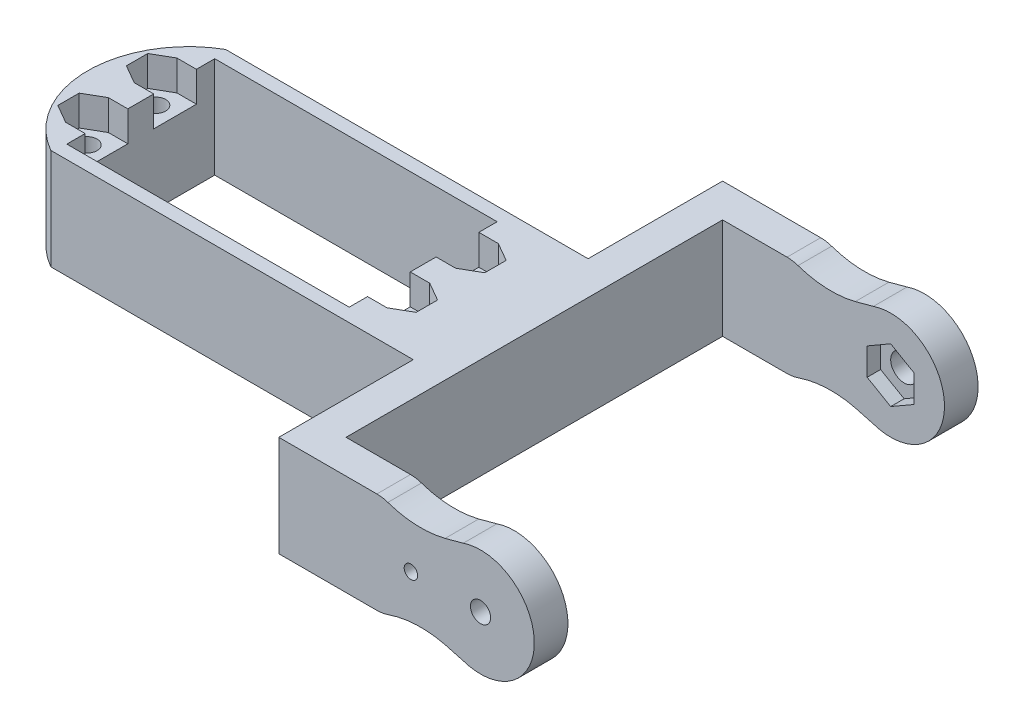
SolidWorks part; units mm, degrees
ref_plane "Plan de face" through (0, 0, 0) normal (0, 0, 1) x (1, 0, 0)
ref_plane "Plan de dessus" through (0, 0, 0) normal (0, 1, 0) x (1, 0, 0)
ref_plane "Plan de droite" through (0, 0, 0) normal (1, 0, 0) x (0, 0, -1)
sketch "Esquisse1" plane through (0, 0, 0) normal (0, 0, 1) x (1, 0, 0)
  line L1 (-23.2387, 9.5601) -> (56.7613, 9.5601)
  line L2 (-23.2387, 9.5601) -> (-23.2387, -16.4399)
  line L3 (-23.2387, -16.4399) -> (56.7613, -16.4399)
  line L4 (56.7613, 9.5601) -> (56.7613, -16.4399)
  dimension "D1" = 26
  dimension "D2" = 80
extrude "Boss.-Extru.1" add sketch "Esquisse1" along normal blind 5
sketch "Esquisse4" plane through (0, 0, 0) normal (0, 0, -1) x (-1, 0, 0)
  line L0 (23.2387, 9.5601) -> (23.2387, -16.4399) construction
  line L1 (38.2387, -13.9399) -> (23.2387, -13.9399)
  line L2 (38.2387, -13.9399) -> (38.2387, 7.0601)
  line L3 (38.2387, 7.0601) -> (23.2387, 7.0601)
  line L4 (23.2387, -13.9399) -> (23.2387, 7.0601)
  line L5 (23.2387, -16.4399) -> (-56.7613, -16.4399) construction
  line L6 (-56.7613, 9.5601) -> (23.2387, 9.5601) construction
  dimension "D1" = 0
  dimension "D2" = 2.5
  dimension "D3" = 2.5
  dimension "D4" = 15
extrude "Boss.-Extru.2" add sketch "Esquisse4" against normal blind 23
sketch "Esquisse6" plane through (0, -13.9399, 0) normal (0, -1, 0) x (1, 0, 0)
  line L0 (-23.2387, 23) -> (-23.2387, 5) construction
  line L1 (-23.2387, 0) -> (-38.2387, 0) construction
  circle A0 centre (-28.7387, 5) radius 1.9
  dimension "D2" = 5
  dimension "D3" = 3.8
  dimension "D1" = 5.5
extrude "Enlèv. mat.-Extru.1" cut sketch "Esquisse6" against normal blind 23
sketch "Esquisse7" plane through (0, 0, 23) normal (0, 0, 1) x (1, 0, 0)
  line L0 (-23.2387, 7.0601) -> (-23.2387, -13.9399) construction
  line L1 (-38.2387, 7.0601) -> (-23.2387, 7.0601) construction
  circle A0 centre (-33.2387, -3.4399) radius 2.5
  dimension "D1" = 5
  dimension "D2" = 10
  dimension "D3" = 10.5
extrude "Enlèv. mat.-Extru.2" cut sketch "Esquisse7" against normal blind 33
sketch "Esquisse8" plane through (0, 0, 0) normal (0, 0, -1) x (-1, 0, 0)
  line L0 (23.2387, -13.9399) -> (38.2387, -13.9399) construction
  line L1 (50.0831, -10.9399) -> (26.2387, -10.9399)
  line L2 (50.0831, -10.9399) -> (50.0831, 4.0601)
  line L3 (50.0831, 4.0601) -> (26.2387, 4.0601)
  line L4 (26.2387, -10.9399) -> (26.2387, 4.0601)
  line L5 (38.2387, 7.0601) -> (23.2387, 7.0601) construction
  line L6 (23.2387, -13.9399) -> (23.2387, -16.4399) construction
  dimension "D1" = 3
  dimension "D2" = 3
  dimension "D3" = 3
extrude "Enlèv. mat.-Extru.3" cut sketch "Esquisse8" against normal blind 20
sketch "Esquisse9" plane through (0, 0, 0) normal (0, 0, -1) x (-1, 0, 0)
  line L19 (38.2387, -13.9399) -> (38.2387, -10.9399)
  line L20 (38.2387, -10.9399) -> (26.2387, -10.9399)
  line L21 (26.2387, -10.9399) -> (26.2387, 4.0601)
  line L22 (26.2387, 4.0601) -> (38.2387, 4.0601)
  line L23 (38.2387, 4.0601) -> (38.2387, 7.0601)
  line L24 (38.2387, 7.0601) -> (23.2387, 7.0601)
  line L25 (23.2387, 7.0601) -> (23.2387, 9.5601)
  line L26 (23.2387, 9.5601) -> (-56.7613, 9.5601)
  line L27 (-56.7613, 9.5601) -> (-56.7613, -16.4399)
  line L28 (-56.7613, -16.4399) -> (23.2387, -16.4399)
  line L29 (23.2387, -16.4399) -> (23.2387, -13.9399)
  line L30 (23.2387, -13.9399) -> (38.2387, -13.9399)
  line L37 (23.2387, 7.0601) -> (23.2387, 9.5601)
  line L38 (23.2387, 9.5601) -> (17.8135, 9.5601)
  line L40 (17.8135, -16.4399) -> (23.2387, -16.4399)
  line L41 (23.2387, -16.4399) -> (23.2387, -13.9399)
  arc A3 (17.8135, -16.4399) -> (23.2387, -13.9399) centre (17.8135, -9.3033) ccw
  arc A4 (17.8135, 9.5601) -> (23.2387, 7.0601) centre (17.8135, 2.4236) cw
  dimension "D1" = 0
extrude "Enlèv. mat.-Extru.4" cut sketch "Esquisse9" against normal blind 20
sketch "Esquisse10" plane through (0, -13.9399, 0) normal (0, -1, 0) x (1, 0, 0)
  line L5 (-38.2387, 0) -> (-23.2387, 0)
  line L6 (-23.2387, 0) -> (-23.2387, 5)
  line L7 (-23.2387, 5) -> (-23.2387, 23)
  line L8 (-23.2387, 23) -> (-38.2387, 23)
  line L9 (-38.2387, 23) -> (-38.2387, 0)
  line L12 (-23.2387, 21.5) -> (-23.2387, 23)
  line L13 (-23.2387, 23) -> (-24.7387, 23)
  arc A0 (-23.2387, 21.5) -> (-24.7387, 23) centre (-24.7387, 21.5) ccw
  dimension "D2" = 3
  dimension "D1" = 0
extrude "Enlèv. mat.-Extru.5" cut sketch "Esquisse10" against normal blind 25
sketch "Esquisse12" plane through (0, -13.9399, 0) normal (0, -1, 0) x (1, 0, 0)
  line L0 (-24.7387, 23) -> (-38.2387, 23) construction
  line L1 (-38.2387, 23) -> (-36.7387, 23)
  line L2 (-38.2387, 23) -> (-38.2387, 21.5)
  arc A0 (-36.7387, 23) -> (-38.2387, 21.5) centre (-36.7387, 21.5) ccw
  dimension "D1" = 3
  dimension "D3" = 1.5
extrude "Enlèv. mat.-Extru.7" cut sketch "Esquisse12" against normal blind 25
sketch "Esquisse13" plane through (0, 7.0601, 0) normal (0, 1, 0) x (1, 0, 0)
  line L1 (-30.7594, -1.5) -> (-32.7801, -5)
  line L2 (-32.7801, -5) -> (-30.7594, -8.5)
  line L3 (-30.7594, -8.5) -> (-26.718, -8.5)
  line L4 (-26.718, -8.5) -> (-24.6972, -5)
  line L5 (-24.6972, -5) -> (-26.718, -1.5)
  line L6 (-26.718, -1.5) -> (-30.7594, -1.5)
  circle A0 centre (-28.7387, -5) radius 3.5 construction
  circle A1 centre (-28.7387, -5) radius 1.9 construction
  dimension "D1" = 7
extrude "Enlèv. mat.-Extru.8" cut sketch "Esquisse13" against normal blind 1
sketch "Esquisse14" plane through (0, 7.0601, 0) normal (0, 1, 0) x (1, 0, 0)
  line L0 (-30.7594, -1.5) -> (-32.7801, -5) construction
  line L1 (-26.718, -1.5) -> (-30.7594, -1.5) construction
  line L2 (-24.6972, -5) -> (-26.718, -1.5) construction
  line L3 (-26.718, -8.5) -> (-24.6972, -5) construction
  line L4 (-30.7594, -8.5) -> (-26.718, -8.5) construction
  line L6 (-25.8519, 0) -> (-31.6254, 0)
  line L7 (-31.6254, 0) -> (-34.5122, -5)
  line L8 (-34.5122, -5) -> (-31.6254, -10)
  line L9 (-31.6254, -10) -> (-25.8519, -10)
  line L15 (-32.7801, -5) -> (-30.7594, -8.5) construction
  line L16 (-30.7594, -1.5) -> (-32.7801, -5)
  line L17 (-26.718, -1.5) -> (-30.7594, -1.5)
  line L18 (-24.6972, -5) -> (-26.718, -1.5)
  line L19 (-26.718, -8.5) -> (-24.6972, -5)
  line L20 (-30.7594, -8.5) -> (-26.718, -8.5)
  line L21 (-32.7801, -5) -> (-30.7594, -8.5)
  line L22 (-25.8519, -10) -> (-23.2387, -5.4737)
  line L27 (-23.2387, -4.5263) -> (-25.8519, 0)
  line L28 (-38.2387, 0) -> (-23.2387, 0) construction
  line L29 (-23.2387, -4.5263) -> (-23.2387, -5.4737)
  line L30 (-23.2387, -21.5) -> (-23.2387, -5) construction
  circle A1 centre (-28.7387, -5) radius 5 construction
  circle A2 centre (-28.7387, -5) radius 1.9 construction
extrude "Boss.-Extru.3" add sketch "Esquisse14" along normal blind 2
sketch "Esquisse15" plane through (0, 0, 0) normal (0, 0, -1) x (-1, 0, 0)
  circle A7 centre (-51.7613, -8.5399) radius 1.5
  circle A8 centre (-51.7613, 1.6601) radius 1.5
  circle A9 centre (-3.9613, -8.5399) radius 1.5
  circle A10 centre (-3.9613, 1.6601) radius 1.5
  dimension "D10" = 3
extrude "Enlèv. mat.-Extru.9" cut sketch "Esquisse15" against normal blind 19
sketch "Esquisse16" plane through (0, 0, 0) normal (0, 0, -1) x (-1, 0, 0)
  line L0 (17.8135, -16.4399) -> (-56.7613, -16.4399) construction
  line L1 (-56.7613, -16.4399) -> (-56.7613, 9.5601) construction
  line L2 (-43.3764, 11.4729) -> (-43.3764, 11.5601)
  line L3 (-43.3764, -43.1341) -> (-70.7923, -43.1341)
  line L4 (-43.3764, -43.1341) -> (-43.3764, -18.3527)
  line L5 (-43.3764, 11.5601) -> (-70.7923, 11.5601)
  line L6 (-70.7923, -43.1341) -> (-70.7923, 11.5601)
  arc A0 (-43.3764, 11.4729) -> (-43.3764, -18.3527) centre (-41.7613, -3.4399) ccw
  dimension "D1" = 13
  dimension "D2" = 30
  dimension "D3" = 15
extrude "Enlèv. mat.-Extru.10" cut sketch "Esquisse16" against normal blind 19
sketch "Esquisse17" plane through (0, 0, 5) normal (0, 0, 1) x (1, 0, 0)
  line L0 (49.2446, 9.5601) -> (-17.8135, 9.5601) construction
  line L1 (6.8613, 7.5601) -> (48.8613, 7.5601)
  line L2 (6.8613, 7.5601) -> (6.8613, -14.4399)
  line L3 (6.8613, -14.4399) -> (48.8613, -14.4399)
  line L4 (48.8613, 7.5601) -> (48.8613, -14.4399)
  circle A0 centre (3.9613, 1.6601) radius 1.5 construction
  dimension "D4" = 2.9
  dimension "D1" = 42
  dimension "D2" = 22
  dimension "D3" = 2
extrude "Enlèv. mat.-Extru.11" cut sketch "Esquisse17" against normal blind 19
sketch "Esquisse18" plane through (0, 0, 0) normal (0, 0, -1) x (-1, 0, 0)
  line L13 (-49.0113, 3.2479) -> (-51.7613, 4.8356)
  line L14 (-51.7613, 4.8356) -> (-54.5113, 3.2479)
  line L15 (-54.5113, 3.2479) -> (-54.5113, 0.0724)
  line L16 (-54.5113, 0.0724) -> (-51.7613, -1.5153)
  line L17 (-51.7613, -1.5153) -> (-49.0113, 0.0724)
  line L19 (-49.0113, -6.9521) -> (-51.7613, -5.3644)
  line L20 (-51.7613, -5.3644) -> (-54.5113, -6.9521)
  line L21 (-54.5113, -6.9521) -> (-54.5113, -10.1276)
  line L22 (-54.5113, -10.1276) -> (-51.7613, -11.7153)
  line L23 (-51.7613, -11.7153) -> (-49.0113, -10.1276)
  line L25 (-49.0113, -10.1276) -> (-46.2613, -8.5399)
  line L26 (-46.2613, -8.5399) -> (-49.0113, -6.9521)
  line L28 (-49.0113, 3.2479) -> (-46.2613, 1.6601)
  line L29 (-49.0113, 0.0724) -> (-46.2613, 1.6601)
  line L30 (-49.0113, -10.1276) -> (-49.0113, -8.5399) [skipped]
  line L31 (-49.0113, 0.0724) -> (-49.0113, 1.6601) [skipped]
  line L33 (-6.7113, 0.0724) -> (-9.4613, 1.6601)
  line L34 (-6.7113, 3.2479) -> (-9.4613, 1.6601)
  line L35 (-9.4613, -8.5399) -> (-6.7113, -6.9521)
  line L36 (-6.7113, -10.1276) -> (-9.4613, -8.5399)
  line L37 (-3.9613, -11.7153) -> (-6.7113, -10.1276)
  line L38 (-1.2113, -10.1276) -> (-3.9613, -11.7153)
  line L39 (-1.2113, -6.9521) -> (-1.2113, -10.1276)
  line L40 (-3.9613, -5.3644) -> (-1.2113, -6.9521)
  line L41 (-6.7113, -6.9521) -> (-3.9613, -5.3644)
  line L42 (-3.9613, -1.5153) -> (-6.7113, 0.0724)
  line L43 (-1.2113, 0.0724) -> (-3.9613, -1.5153)
  line L44 (-1.2113, 3.2479) -> (-1.2113, 0.0724)
  line L45 (-3.9613, 4.8356) -> (-1.2113, 3.2479)
  line L46 (-6.7113, 3.2479) -> (-3.9613, 4.8356)
  arc A0 (-5.3363, -6.1583) -> (-5.3363, -10.9214) centre (-3.9613, -8.5399) cw construction
  arc A1 (-5.3363, 4.0417) -> (-5.3363, -0.7214) centre (-3.9613, 1.6601) cw construction
  arc A2 (-50.3863, 4.0417) -> (-50.3863, -0.7214) centre (-51.7613, 1.6601) ccw construction
  arc A3 (-50.3863, -6.1583) -> (-50.3863, -10.9214) centre (-51.7613, -8.5399) ccw construction
  circle A6 centre (-51.7613, 1.6601) radius 1.5 construction
  circle A7 centre (-51.7613, -8.5399) radius 1.5 construction
  dimension "D1" = 5.5
  dimension "D2" = 5.5
extrude "Enlèv. mat.-Extru.12" cut sketch "Esquisse18" against normal blind 2
sketch "Esquisse19" plane through (0, 0, 0) normal (0, 0, -1) x (-1, 0, 0)
  line L9 (-12.8613, -16.4399) -> (-22.8613, -16.4399)
  line L12 (-11.8613, -15.4399) -> (-11.8613, -14.4399)
  line L13 (-11.8613, -14.4399) -> (-23.8613, -14.4399)
  line L21 (-23.8613, -15.4399) -> (-23.8613, -14.4399)
  line L22 (-6.8613, -10.041) -> (-6.8613, -14.4399) construction
  line L23 (-6.8613, -14.4399) -> (-48.8613, -14.4399) construction
  line L24 (17.8135, -16.4399) -> (-49.2446, -16.4399) construction
  line L27 (-23.8613, 8.5601) -> (-23.8613, 7.5601)
  line L28 (-11.8613, 7.5601) -> (-23.8613, 7.5601)
  line L29 (-11.8613, 8.5601) -> (-11.8613, 7.5601)
  line L30 (-12.8613, 9.5601) -> (-22.8613, 9.5601)
  arc A2 (-12.8613, -16.4399) -> (-11.8613, -15.4399) centre (-12.8613, -15.4399) ccw
  arc A3 (-23.8613, -15.4399) -> (-22.8613, -16.4399) centre (-22.8613, -15.4399) ccw
  arc A6 (-23.8613, 8.5601) -> (-22.8613, 9.5601) centre (-22.8613, 8.5601) cw
  arc A7 (-12.8613, 9.5601) -> (-11.8613, 8.5601) centre (-12.8613, 8.5601) cw
  point P4 (-17.8613, -16.4399)
  dimension "D3" = 0
  dimension "D4" = 0
  dimension "D5" = 2
  dimension "D1" = 10
  dimension "D2" = 11
  dimension "D6" = 2
extrude "Boss.-Extru.4" add sketch "Esquisse19" along normal blind 22
sketch "Esquisse23" plane through (0, 0, -22) normal (0, 0, -1) x (-1, 0, 0)
  line L0 (-6.8613, -10.041) -> (-6.8613, -14.4399) construction
  line L4 (-23.8613, 8.5601) -> (-23.8613, 7.5601)
  line L5 (-23.8613, 7.5601) -> (-11.8613, 7.5601)
  line L6 (-11.8613, 7.5601) -> (-11.8613, 8.5601)
  line L7 (-12.8613, 9.5601) -> (-22.8613, 9.5601)
  line L8 (-23.8613, 8.5601) -> (-23.8613, 7.5601)
  line L10 (-11.8613, 7.5601) -> (-11.8613, 8.5601)
  line L11 (-12.8613, 9.5601) -> (-22.8613, 9.5601)
  line L12 (-22.8613, -16.4399) -> (-12.8613, -16.4399)
  line L13 (-11.8613, -15.4399) -> (-11.8613, -14.4399)
  line L14 (-11.8613, -14.4399) -> (-23.8613, -14.4399)
  line L15 (-23.8613, -14.4399) -> (-23.8613, -15.4399)
  line L16 (-22.8613, -16.4399) -> (-12.8613, -16.4399)
  line L17 (-11.8613, -15.4399) -> (-11.8613, -14.4399)
  line L19 (-23.8613, -14.4399) -> (-23.8613, -15.4399)
  line L21 (-6.8613, -14.4399) -> (-11.8613, -14.4399) construction
  arc A0 (-10.1971, -9.8632) -> (-10.1971, 2.9835) centre (-17.8613, -3.4399) ccw
  arc A1 (-11.8613, 7.5601) -> (-10.1971, 2.9835) centre (-4.7363, 7.5601) ccw
  arc A2 (-22.8613, 9.5601) -> (-23.8613, 8.5601) centre (-22.8613, 8.5601) ccw
  arc A3 (-11.8613, 8.5601) -> (-12.8613, 9.5601) centre (-12.8613, 8.5601) ccw
  arc A4 (-22.8613, 9.5601) -> (-23.8613, 8.5601) centre (-22.8613, 8.5601) ccw
  arc A5 (-11.8613, 8.5601) -> (-12.8613, 9.5601) centre (-12.8613, 8.5601) ccw
  arc A6 (-23.8613, -15.4399) -> (-22.8613, -16.4399) centre (-22.8613, -15.4399) ccw
  arc A7 (-12.8613, -16.4399) -> (-11.8613, -15.4399) centre (-12.8613, -15.4399) ccw
  arc A8 (-23.8613, -15.4399) -> (-22.8613, -16.4399) centre (-22.8613, -15.4399) ccw
  arc A9 (-12.8613, -16.4399) -> (-11.8613, -15.4399) centre (-12.8613, -15.4399) ccw
  arc A10 (-23.8613, 7.5601) -> (-25.5255, 2.9835) centre (-30.9863, 7.5601) cw
  arc A11 (-23.8613, -14.4399) -> (-25.5255, -9.8632) centre (-30.9863, -14.4399) ccw
  arc A12 (-11.8613, -14.4399) -> (-10.1971, -9.8632) centre (-4.7363, -14.4399) cw
  arc A13 (-25.5255, 2.9835) -> (-25.5255, -9.8632) centre (-17.8613, -3.4399) ccw
  dimension "D3" = 20
  dimension "D5" = 11
  dimension "D4" = 11
  dimension "D1" = 0
  dimension "D2" = 0
extrude "Boss.-Extru.5" add sketch "Esquisse23" along normal blind 10
sketch "Esquisse25" plane through (0, 0, -32) normal (0, 0, -1) x (-1, 0, 0)
  circle A0 centre (-17.8613, -3.4399) radius 8
  arc A1 (-10.1971, -9.8632) -> (-10.1971, 2.9835) centre (-17.8613, -3.4399) ccw construction
  dimension "D1" = 16
extrude "Enlèv. mat.-Extru.13" cut sketch "Esquisse25" against normal blind 5
sketch "Esquisse26" plane through (0, 0, -27) normal (0, 0, -1) x (-1, 0, 0)
  circle A0 centre (-17.8613, -3.4399) radius 6
  circle A1 centre (-17.8613, -3.4399) radius 8 construction
  dimension "D1" = 12
extrude "Enlèv. mat.-Extru.14" cut sketch "Esquisse26" against normal blind 5
sketch "Esquisse29" plane through (0, -13.9399, 0) normal (0, -1, 0) x (1, 0, 0)
  line L0 (-23.2387, 0) -> (-38.2387, 0) construction
  line L1 (-26.718, 1.5) -> (-24.6972, 5)
  line L2 (-24.6972, 5) -> (-26.718, 8.5)
  line L3 (-26.718, 8.5) -> (-30.7594, 8.5)
  line L4 (-30.7594, 8.5) -> (-32.7801, 5)
  line L5 (-32.7801, 5) -> (-30.7594, 1.5)
  line L6 (-30.7594, 1.5) -> (-26.718, 1.5)
  circle A0 centre (-28.7387, 5) radius 3.5 construction
  circle A1 centre (-28.7387, 5) radius 1.9 construction
  dimension "D1" = 7
extrude "Enlèv. mat.-Extru.15" cut sketch "Esquisse29" against normal blind 1
sketch "Esquisse32" plane through (0, -13.9399, 0) normal (0, -1, 0) x (1, 0, 0)
  line L0 (-26.718, 8.5) -> (-30.7594, 8.5) construction
  line L1 (-25.8519, 0) -> (-23.2387, 4.5263)
  line L2 (-23.2387, 5.4737) -> (-25.8519, 10)
  line L3 (-25.8519, 10) -> (-31.6254, 10)
  line L4 (-31.6254, 10) -> (-34.5122, 5)
  line L5 (-34.5122, 5) -> (-31.6254, 0)
  line L6 (-31.6254, 0) -> (-25.8519, 0)
  line L7 (-26.718, 1.5) -> (-24.6972, 5)
  line L8 (-24.6972, 5) -> (-26.718, 8.5)
  line L9 (-26.718, 8.5) -> (-30.7594, 8.5)
  line L10 (-30.7594, 8.5) -> (-32.7801, 5)
  line L11 (-32.7801, 5) -> (-30.7594, 1.5)
  line L12 (-30.7594, 1.5) -> (-26.718, 1.5)
  line L13 (-23.2387, 0) -> (-38.2387, 0) construction
  line L14 (-23.2387, 5.4737) -> (-23.2387, 4.5263)
  line L15 (-23.2387, 21.5) -> (-23.2387, 5) construction
  circle A0 centre (-28.7387, 5) radius 5 construction
  circle A1 centre (-28.7387, 5) radius 3.5 construction
  circle A2 centre (-28.7387, 5) radius 1.9 construction
extrude "Boss.-Extru.6" add sketch "Esquisse32" along normal blind 2
sketch "Esquisse33" plane through (0, 0, 5) normal (0, 0, 1) x (1, 0, 0)
  line L1 (6.478, -16.4399) -> (-54.7028, -16.4399)
  line L3 (6.478, 9.5601) -> (-54.7028, 9.5601)
  line L4 (-54.7028, -16.4399) -> (-54.7028, 9.5601)
  arc A2 (6.478, -16.4399) -> (6.478, 9.5601) centre (13.9613, -3.4399) cw
extrude "Enlèv. mat.-Extru.16" cut sketch "Esquisse33" along normal blind 25 and the other way blind 25
sketch "Esquisse34" plane through (0, 0, 5) normal (0, 0, 1) x (1, 0, 0)
  line L1 (59.2446, -16.4399) -> (49.2446, -16.4399)
  line L2 (59.2446, -16.4399) -> (59.2446, 9.5601)
  line L3 (59.2446, 9.5601) -> (49.2446, 9.5601)
  arc A0 (49.2446, -16.4399) -> (49.2446, 9.5601) centre (41.7613, -3.4399) ccw construction
  arc A1 (49.2446, -16.4399) -> (49.2446, 9.5601) centre (41.7613, -3.4399) ccw
  dimension "D1" = 10
extrude "Boss.-Extru.7" add sketch "Esquisse34" against normal blind 5
sketch "Esquisse35" plane through (0, 0, 5) normal (0, 0, 1) x (1, 0, 0)
  line L1 (62.7446, -9.4399) -> (59.2446, -9.4399)
  line L2 (64.2446, -7.9399) -> (64.2446, 1.0601)
  line L3 (62.7446, 2.5601) -> (59.2446, 2.5601)
  line L4 (59.2446, -9.4399) -> (59.2446, 2.5601)
  line L5 (48.8613, 7.5601) -> (6.8613, 7.5601) construction
  line L6 (59.2446, -16.4399) -> (59.2446, 9.5601) construction
  arc A0 (62.7446, -9.4399) -> (64.2446, -7.9399) centre (62.7446, -7.9399) ccw
  arc A1 (64.2446, 1.0601) -> (62.7446, 2.5601) centre (62.7446, 1.0601) ccw
  point P4 (59.2446, -3.4399)
  dimension "D5" = 3
  dimension "D6" = 1.5
  dimension "D7" = 1.5
  dimension "D8" = 1.5
  dimension "D9" = 1.5
  dimension "D10" = 3
  dimension "D1" = 12
  dimension "D2" = 11
  dimension "D3" = 0
extrude "Boss.-Extru.8" add sketch "Esquisse35" against normal blind 43 and the other way blind 23
sketch "Esquisse36" plane through (64.2446, 0, 0) normal (1, 0, 0) x (0, 0, -1)
  line L0 (-28, -9.4399) -> (38, -9.4399) construction
  line L1 (33.5, 2.5601) -> (38, 2.5601)
  line L2 (32, 1.0601) -> (32, -7.9399)
  line L3 (33.5, -9.4399) -> (38, -9.4399)
  line L4 (38, 2.5601) -> (38, -9.4399)
  line L5 (-28, 2.5601) -> (38, 2.5601) construction
  line L6 (38, -7.9399) -> (38, 1.0601) construction
  line L10 (-28, 2.5601) -> (-28, -9.4399)
  line L11 (-23.5, -9.4399) -> (-28, -9.4399)
  line L12 (-22, 1.0601) -> (-22, -7.9399)
  line L13 (-23.5, 2.5601) -> (-28, 2.5601)
  arc A0 (32, -7.9399) -> (33.5, -9.4399) centre (33.5, -7.9399) ccw
  arc A1 (33.5, 2.5601) -> (32, 1.0601) centre (33.5, 1.0601) ccw
  arc A2 (-23.5, 2.5601) -> (-22, 1.0601) centre (-23.5, 1.0601) cw
  arc A3 (-22, -7.9399) -> (-23.5, -9.4399) centre (-23.5, -7.9399) cw
  dimension "D2" = 3
  dimension "D3" = 3
extrude "Boss.-Extru.10" add sketch "Esquisse36" along normal blind 45 and the other way blind 3
sketch "Esquisse39" plane through (0, 0, -38) normal (0, 0, -1) x (-1, 0, 0)
  line L1 (-109.2446, 2.5601) -> (-59.2446, 2.5601) construction
  line L2 (-109.2446, -9.4399) -> (-109.2446, 2.5601) construction
  line L4 (-77.7127, 2.5601) -> (-100.2936, 2.5601)
  line L5 (-77.7127, 2.5601) -> (-77.7127, -9.4399)
  line L6 (-77.7127, -9.4399) -> (-100.2936, -9.4399)
  arc A0 (-106.9085, 4.2114) -> (-106.9085, -11.0912) centre (-109.2446, -3.4399) ccw
  spline S0 degree 3 poles (-106.9085, -11.0912) (-104.6699, -10.4077) (-102.4654, -9.859) (-100.2936, -9.4399) knots 0 0 0 0 0.141371 0.141371 0.141371 0.141371
  spline S1 degree 3 poles (-106.9085, 4.2114) (-104.6699, 3.5279) (-102.4654, 2.9793) (-100.2936, 2.5601) knots 0 0 0 0 0.141371 0.141371 0.141371 0.141371
  dimension "D1" = 16
  dimension "D2" = 6
  dimension "D3" = 0
  dimension "D6" = 0
extrude "Boss.-Extru.12" add sketch "Esquisse39" against normal blind 5
sketch "Esquisse40" plane through (109.2446, 0, 0) normal (1, 0, 0) x (0, 0, -1)
  line L2 (33, -9.3541) -> (33, 2.4744)
  line L3 (32, 1.0601) -> (32, -7.9399)
  line L4 (33, -9.3541) -> (33, 2.4744)
  line L5 (32, 1.0601) -> (32, -7.9399)
  arc A2 (32, -7.9399) -> (33, -9.3541) centre (33.5, -7.9399) ccw
  arc A3 (33, 2.4744) -> (32, 1.0601) centre (33.5, 1.0601) ccw
  arc A4 (32, -7.9399) -> (33, -9.3541) centre (33.5, -7.9399) ccw
  arc A5 (33, 2.4744) -> (32, 1.0601) centre (33.5, 1.0601) ccw
  dimension "D1" = 0
extrude "Enlèv. mat.-Extru.18" cut sketch "Esquisse40" against normal blind 45
sketch "Esquisse41" plane through (59.2446, 0, 0) normal (-1, 0, 0) x (0, 0, 1)
  line L0 (0, 2.5601) -> (-38, 2.5601) construction
  line L1 (-38, -9.4399) -> (-33, -9.4399)
  line L2 (-38, -9.4399) -> (-38, 2.5601)
  line L3 (-38, 2.5601) -> (-33, 2.5601)
  line L4 (-33, -9.4399) -> (-33, 2.5601)
  line L5 (-38, 2.5601) -> (-38, -9.4399) construction
  line L6 (0, -9.4399) -> (-38, -9.4399) construction
  dimension "D1" = 5
extrude "Boss.-Extru.13" add sketch "Esquisse41" against normal blind 37
sketch "Esquisse42" plane through (0, 0, -33) normal (0, 0, 1) x (1, 0, 0)
  line L1 (105.7446, -5.4606) -> (109.2446, -7.4813)
  line L2 (109.2446, -7.4813) -> (112.7446, -5.4606)
  line L3 (112.7446, -5.4606) -> (112.7446, -1.4191)
  line L4 (112.7446, -1.4191) -> (109.2446, 0.6016)
  line L5 (109.2446, 0.6016) -> (105.7446, -1.4191)
  line L6 (105.7446, -1.4191) -> (105.7446, -5.4606)
  circle A0 centre (109.2446, -3.4399) radius 3.5 construction
  arc A1 (106.9085, -11.0912) -> (106.9085, 4.2114) centre (109.2446, -3.4399) ccw construction
  dimension "D1" = 7
extrude "Enlèv. mat.-Extru.19" cut sketch "Esquisse42" against normal blind 2
sketch "Esquisse43" plane through (0, 0, -38) normal (0, 0, -1) x (-1, 0, 0)
  circle A0 centre (-109.2446, -3.4399) radius 2
  arc A2 (-106.9085, 4.2114) -> (-106.9085, -11.0912) centre (-109.2446, -3.4399) ccw construction
  dimension "D1" = 4
extrude "Enlèv. mat.-Extru.20" cut sketch "Esquisse43" against normal blind 18
sketch "Esquisse44" plane through (0, 0, 28) normal (0, 0, 1) x (1, 0, 0)
  line L1 (117.9958, 12.8483) -> (93.3939, 12.8483)
  line L2 (117.9958, 12.8483) -> (117.9958, -24.309)
  line L3 (117.9958, -24.309) -> (93.3939, -24.309)
  line L4 (93.3939, 12.8483) -> (93.3939, -24.309)
extrude "Enlèv. mat.-Extru.21" cut sketch "Esquisse44" against normal blind 18
sketch "Esquisse45" plane through (0, 0, 28) normal (0, 0, 1) x (1, 0, 0)
  line L5 (100.2936, 2.5601) -> (62.7446, 2.5601)
  line L6 (63.2446, 2.4744) -> (64.2446, 2.4744)
  line L7 (64.2446, 2.4744) -> (64.2446, -9.3541)
  line L8 (64.2446, -9.3541) -> (63.2446, -9.3541)
  line L9 (62.7446, -9.4399) -> (100.2936, -9.4399)
  line L10 (100.2936, 2.5601) -> (62.7446, 2.5601)
  line L11 (63.2446, 2.4744) -> (64.2446, 2.4744)
  line L12 (64.2446, 2.4744) -> (64.2446, -9.3541)
  line L13 (64.2446, -9.3541) -> (63.2446, -9.3541)
  line L14 (62.7446, -9.4399) -> (100.2936, -9.4399)
  circle A0 centre (109.2446, -3.4399) radius 1.5
  circle A1 centre (109.2446, -3.4399) radius 2 construction
  circle A2 centre (98.8946, -3.4399) radius 1
  arc A7 (63.2446, 2.4744) -> (62.7446, 2.5601) centre (62.7446, 1.0601) ccw
  arc A8 (62.7446, -9.4399) -> (63.2446, -9.3541) centre (62.7446, -7.9399) ccw
  arc A9 (106.9085, -11.0912) -> (106.9085, 4.2114) centre (109.2446, -3.4399) ccw
  arc A10 (63.2446, 2.4744) -> (62.7446, 2.5601) centre (62.7446, 1.0601) ccw
  arc A11 (62.7446, -9.4399) -> (63.2446, -9.3541) centre (62.7446, -7.9399) ccw
  arc A12 (106.9085, -11.0912) -> (106.9085, 4.2114) centre (109.2446, -3.4399) ccw
  spline S2 degree 3 poles (1174.2572, 2799.09) (-736.5679, -3514.3896) (680.2206, 3802.3628) (-1163.3937, -2641.5643) knots -8.562357 -8.562357 -8.562357 -8.562357 15.816442 15.816442 15.816442 15.816442 only from (106.9085, 4.2114) to (100.2936, 2.5601)
  spline S3 degree 3 poles (-1163.4194, 2634.7746) (680.24, -3809.3321) (-736.5862, 3507.588) (1174.2763, -2806.0329) knots -15.675185 -15.675185 -15.675185 -15.675185 8.703809 8.703809 8.703809 8.703809 only from (100.2936, -9.4399) to (106.9085, -11.0912)
  spline S4 degree 3 poles (106.9085, 4.2114) (104.6699, 3.5279) (102.4654, 2.9793) (100.2936, 2.5601) knots 0 0 0 0 0.141371 0.141371 0.141371 0.141371
  spline S5 degree 3 poles (100.2936, -9.4399) (102.4654, -9.859) (104.6699, -10.4077) (106.9085, -11.0912) knots 0 0 0 0 0.141371 0.141371 0.141371 0.141371
  dimension "D1" = 3
  dimension "D2" = 2
  dimension "D3" = 0
  dimension "D4" = 10.35
  dimension "D6" = 37.549
  dimension "D5" = 0
extrude "Boss.-Extru.14" add sketch "Esquisse45" against normal blind 5
sketch "Esquisse46" plane through (93.3939, 0, 0) normal (1, 0, 0) x (0, 0, -1)
  line L2 (-23, 2.4744) -> (-23, -9.3541)
  line L3 (-22, -7.9399) -> (-22, 1.0601)
  line L4 (-23, 2.4744) -> (-23, -9.3541)
  line L5 (-22, -7.9399) -> (-22, 1.0601)
  arc A2 (-23, -9.3541) -> (-22, -7.9399) centre (-23.5, -7.9399) ccw
  arc A3 (-22, 1.0601) -> (-23, 2.4744) centre (-23.5, 1.0601) ccw
  arc A4 (-23, -9.3541) -> (-22, -7.9399) centre (-23.5, -7.9399) ccw
  arc A5 (-22, 1.0601) -> (-23, 2.4744) centre (-23.5, 1.0601) ccw
  dimension "D1" = 0
extrude "Enlèv. mat.-Extru.22" cut sketch "Esquisse46" against normal blind 29
sketch "Esquisse47" plane through (0, 0, 22) normal (0, 0, -1) x (-1, 0, 0)
  line L4 (-64.2446, 1.0601) -> (-64.3939, 1.0601)
  line L5 (-64.3939, 1.0601) -> (-64.3939, -7.9399)
  line L6 (-64.3939, -7.9399) -> (-64.2446, -7.9399)
  line L7 (-64.2446, -7.9399) -> (-64.2446, 1.0601)
  line L8 (-64.2446, 1.0601) -> (-64.3939, 1.0601)
  line L9 (-64.3939, 1.0601) -> (-64.3939, -7.9399)
  line L10 (-64.3939, -7.9399) -> (-64.2446, -7.9399)
  line L11 (-64.2446, -7.9399) -> (-64.2446, 1.0601)
  dimension "D1" = 0
extrude "Enlèv. mat.-Extru.23" cut sketch "Esquisse47" against normal blind 1
sketch "Esquisse48" plane through (0, 1.0601, 0) normal (0, -1, 0) x (1, 0, 0)
  line L4 (64.2446, 22) -> (64.3939, 22)
  line L5 (64.3939, 22) -> (64.3939, 23)
  line L6 (64.3939, 23) -> (64.2446, 23)
  line L7 (64.2446, 23) -> (64.2446, 22)
  line L8 (64.2446, 22) -> (64.3939, 22)
  line L9 (64.3939, 22) -> (64.3939, 23)
  line L10 (64.3939, 23) -> (64.2446, 23)
  line L11 (64.2446, 23) -> (64.2446, 22)
  dimension "D1" = 0
extrude "Enlèv. mat.-Extru.24" cut sketch "Esquisse48" along normal blind 21 and the other way blind 15
sketch "Esquisse49" plane through (0, 0, 5) normal (0, 0, 1) x (1, 0, 0)
  line L1 (59.2446, 9.5601) -> (6.478, 9.5601) construction
  line L2 (59.2446, -16.4399) -> (59.2446, -9.4399) construction
  line L3 (6.478, -16.4399) -> (59.2446, -16.4399) construction
  line L4 (59.2446, -9.4399) -> (59.2446, -16.4399)
  line L5 (59.2446, 9.5601) -> (52.2446, 9.5601)
  line L6 (59.2446, 9.5601) -> (59.2446, 2.5601)
  line L7 (59.2446, -16.4399) -> (52.2446, -16.4399)
  arc A2 (59.2446, 2.5601) -> (52.2446, 9.5601) centre (52.2446, 2.5601) ccw
  arc A3 (52.2446, -16.4399) -> (59.2446, -9.4399) centre (52.2446, -9.4399) ccw
extrude "Enlèv. mat.-Extru.25" cut sketch "Esquisse49" against normal blind 21
sketch "Esquisse50" plane through (0, 2.5601, 0) normal (0, 1, 0) x (1, 0, 0)
  line L0 (59.2446, -28) -> (59.2446, -5) construction
  line L1 (52.2446, -5) -> (59.2446, -5) construction
  line L4 (59.2446, 5.9833) -> (59.2446, -10.9833)
  line L9 (53.2613, 0) -> (53.2613, -5)
  arc A0 (59.2446, -10.9833) -> (53.2613, -5) centre (53.2613, -10.9833) ccw
  arc A2 (59.2446, 5.9833) -> (53.2613, 0) centre (53.2613, 5.9833) cw
extrude "Boss.-Extru.15" add sketch "Esquisse50" against normal blind 12
sketch "Esquisse51" plane through (0, 0, 0) normal (0, 0, -1) x (-1, 0, 0)
  line L0 (-51.7613, 4.8356) -> (-54.5113, 3.2479) construction
  line L1 (-49.0113, -10.1276) -> (-49.0113, -6.9521)
  line L2 (-49.0113, -6.9521) -> (-51.7613, -5.3644)
  line L3 (-51.7613, -5.3644) -> (-54.5113, -6.9521)
  line L4 (-54.5113, -6.9521) -> (-54.5113, -10.1276)
  line L5 (-54.5113, -10.1276) -> (-51.7613, -11.7153)
  line L6 (-51.7613, -11.7153) -> (-49.0113, -10.1276)
  line L7 (-49.0113, 3.2479) -> (-51.7613, 4.8356)
  line L8 (-51.7613, 4.8356) -> (-54.5113, 3.2479)
  line L9 (-54.5113, 3.2479) -> (-54.5113, 0.0724)
  line L10 (-54.5113, 0.0724) -> (-51.7613, -1.5153)
  line L11 (-51.7613, -1.5153) -> (-49.0113, 0.0724)
  line L12 (-49.0113, 0.0724) -> (-49.0113, 3.2479)
  line L13 (-54.5113, -9.4399) -> (-54.5113, -10.1276) construction
  circle A0 centre (-51.7613, -8.5399) radius 2.75 construction
  circle A1 centre (-51.7613, 1.6601) radius 2.75 construction
  circle A2 centre (-51.7613, 1.6601) radius 1.5 construction
  circle A3 centre (-51.7613, -8.5399) radius 1.5 construction
extrude "Enlèv. mat.-Extru.26" cut sketch "Esquisse51" against normal blind 2 and the other way blind 13
sketch "Esquisse52" plane through (0, 2.5601, 0) normal (0, 1, 0) x (1, 0, 0)
  line L0 (59.2446, -28) -> (59.2446, -10.9833) construction
  line L1 (-19.1574, -30.9233) -> (59.2446, -30.9233)
  line L2 (-19.1574, -30.9233) -> (-19.1574, 44.4632)
  line L3 (-19.1574, 44.4632) -> (59.2446, 44.4632)
  line L4 (59.2446, -30.9233) -> (59.2446, 44.4632)
extrude "Enlèv. mat.-Extru.27" cut sketch "Esquisse52" against normal blind 40 and the other way blind 38
sketch "Esquisse55" plane through (0, -9.4399, 0) normal (0, -1, 0) x (1, 0, 0)
  line L0 (5.3359, -18) -> (51.0541, -18)
  line L1 (5.7192, -16) -> (47.7192, -16)
  line L2 (47.7192, 6) -> (5.7192, 6)
  line L3 (47.7192, -16) -> (47.7192, 6)
  line L5 (48.3958, 8) -> (5.3359, 8)
  line L6 (5.7192, 6) -> (5.7192, -16)
  line L7 (51.0541, -18) -> (59.2446, -18)
  line L8 (48.3958, 8) -> (59.2446, 8)
  line L16 (59.2446, -18) -> (59.2446, 8)
  line L17 (59.2446, 28) -> (59.2446, -38) construction
  line L20 (59.2446, -38) -> (100.2936, -38) construction
  circle A1 centre (50.6192, -10.1) radius 1.5
  circle A2 centre (50.6192, 0.1) radius 1.5
  circle A4 centre (2.8192, 0.1) radius 1.5
  circle A5 centre (2.8192, -10.1) radius 1.5
  arc A6 (5.3359, 8) -> (5.3359, -18) centre (12.8192, -5) ccw
  dimension "D5" = 3
  dimension "D6" = 3
  dimension "D7" = 2.9
  dimension "D8" = 2.9
  dimension "D9" = 2.9
  dimension "D10" = 2.9
  dimension "D11" = 3
  dimension "D12" = 3
  dimension "D1" = 2
  dimension "D2" = 2
  dimension "D3" = 42
  dimension "D4" = 22
  dimension "D14" = 20
  dimension "D15" = 26
extrude "Boss.-Extru.16" add sketch "Esquisse55" against normal blind 12
sketch "Esquisse57" plane through (0, 2.5601, 0) normal (0, 1, 0) x (1, 0, 0)
  line L0 (47.8692, 11.6877) -> (45.1192, 10.1)
  line L2 (47.8692, 8.5123) -> (50.6192, 6.9246)
  line L3 (50.6192, 6.9246) -> (53.3692, 8.5123)
  line L4 (53.3692, 8.5123) -> (53.3692, 11.6877)
  line L5 (53.3692, 11.6877) -> (50.6192, 13.2754)
  line L6 (50.6192, 13.2754) -> (47.8692, 11.6877)
  line L7 (47.8692, 8.5123) -> (45.1192, 10.1)
  line L8 (47.8692, 11.6877) -> (47.8692, 10.1) [skipped]
  line L13 (47.8692, 1.4877) -> (45.1192, -0.1)
  line L14 (50.6192, -3.2754) -> (47.8692, -1.6877)
  line L15 (53.3692, -1.6877) -> (50.6192, -3.2754)
  line L16 (53.3692, 1.4877) -> (53.3692, -1.6877)
  line L17 (50.6192, 3.0754) -> (53.3692, 1.4877)
  line L18 (47.8692, 1.4877) -> (50.6192, 3.0754)
  line L19 (47.8692, -1.6877) -> (45.1192, -0.1)
  line L20 (5.5692, -1.6877) -> (8.3192, -0.1)
  line L21 (5.5692, 1.4877) -> (2.8192, 3.0754)
  line L22 (2.8192, 3.0754) -> (0.0692, 1.4877)
  line L23 (0.0692, 1.4877) -> (0.0692, -1.6877)
  line L24 (0.0692, -1.6877) -> (2.8192, -3.2754)
  line L25 (2.8192, -3.2754) -> (5.5692, -1.6877)
  line L26 (5.5692, 1.4877) -> (8.3192, -0.1)
  line L27 (5.5692, 8.5123) -> (8.3192, 10.1)
  line L28 (2.8192, 13.2754) -> (5.5692, 11.6877)
  line L29 (0.0692, 11.6877) -> (2.8192, 13.2754)
  line L30 (0.0692, 8.5123) -> (0.0692, 11.6877)
  line L31 (2.8192, 6.9246) -> (0.0692, 8.5123)
  line L32 (5.5692, 8.5123) -> (2.8192, 6.9246)
  line L33 (5.5692, 11.6877) -> (8.3192, 10.1)
  arc A0 (49.2442, 7.7184) -> (49.2442, 12.4816) centre (50.6192, 10.1) ccw construction
  circle A1 centre (50.6192, 10.1) radius 1.5 construction
  arc A2 (49.2442, 2.2816) -> (49.2442, -2.4816) centre (50.6192, -0.1) cw construction
  arc A3 (4.1942, 2.2816) -> (4.1942, -2.4816) centre (2.8192, -0.1) ccw construction
  arc A4 (4.1942, 7.7184) -> (4.1942, 12.4816) centre (2.8192, 10.1) cw construction
  dimension "D1" = 5.5
extrude "Enlèv. mat.-Extru.28" cut sketch "Esquisse57" against normal blind 3
sketch "Esquisse58" plane through (0, 2.5601, 0) normal (0, 1, 0) x (1, 0, 0)
  line L0 (50.6192, 13.2754) -> (47.7192, 11.6011) construction
  line L1 (53.3692, -1.6877) -> (53.3692, 1.4877) construction
  line L2 (47.7192, -1.6011) -> (50.6192, -3.2754) construction
  line L3 (50.6192, 3.0754) -> (47.7192, 1.4011) construction
  line L4 (53.3692, 1.4877) -> (50.6192, 3.0754) construction
  line L5 (53.3692, 8.5123) -> (53.3692, 11.6877) construction
  line L6 (50.6192, 6.9246) -> (53.3692, 8.5123) construction
  line L7 (47.7192, 8.5989) -> (50.6192, 6.9246) construction
  line L8 (53.3692, 11.6877) -> (50.6192, 13.2754) construction
  line L9 (53.3692, -1.6877) -> (53.3692, 1.4877)
  line L10 (47.7192, -1.6011) -> (50.6192, -3.2754)
  line L11 (59.2446, -8) -> (59.2446, -28)
  line L12 (59.2446, -28) -> (100.2936, -28)
  line L13 (100.2936, -28) -> (100.2936, -23)
  line L14 (100.2936, -23) -> (62.7446, -23)
  line L15 (62.7446, -23) -> (62.7446, 33)
  line L16 (62.7446, 33) -> (100.2936, 33)
  line L17 (100.2936, 33) -> (100.2936, 38)
  line L18 (100.2936, 38) -> (59.2446, 38)
  line L19 (59.2446, 38) -> (59.2446, 18)
  line L20 (59.2446, 18) -> (5.3359, 18)
  line L21 (5.3359, -8) -> (59.2446, -8)
  line L31 (59.2446, 18) -> (5.3359, 18)
  line L32 (5.3359, -8) -> (59.2446, -8)
  line L33 (50.6192, 3.0754) -> (47.7192, 1.4011)
  line L34 (53.3692, 1.4877) -> (50.6192, 3.0754)
  line L35 (53.3692, 8.5123) -> (53.3692, 11.6877)
  line L36 (50.6192, 6.9246) -> (53.3692, 8.5123)
  line L37 (47.7192, 8.5989) -> (50.6192, 6.9246)
  line L38 (50.6192, 13.2754) -> (47.7192, 11.6011)
  line L39 (53.3692, 11.6877) -> (50.6192, 13.2754)
  line L40 (50.6192, -3.2754) -> (53.3692, -1.6877) construction
  line L41 (50.6192, -3.2754) -> (53.3692, -1.6877)
  line L42 (47.7192, 8.5989) -> (47.7192, 1.4011) construction
  line L43 (47.7192, 8.5989) -> (47.7192, 1.4011)
  line L44 (47.7192, 16) -> (47.7192, 11.6011) construction
  line L45 (47.7192, 16) -> (47.7192, 11.6011)
  line L46 (5.7192, 16) -> (47.7192, 16) construction
  line L47 (5.7192, 16) -> (47.7192, 16)
  line L48 (47.7192, -6) -> (5.7192, -6) construction
  line L49 (47.7192, -6) -> (5.7192, -6)
  line L50 (47.7192, -1.6011) -> (47.7192, -6) construction
  line L51 (47.7192, -1.6011) -> (47.7192, -6)
  line L52 (5.7192, 11.6011) -> (2.8192, 13.2754) construction
  line L53 (2.8192, 13.2754) -> (0.0692, 11.6877) construction
  line L54 (0.0692, 11.6877) -> (0.0692, 8.5123) construction
  line L55 (0.0692, 8.5123) -> (2.8192, 6.9246) construction
  line L56 (2.8192, 6.9246) -> (5.7192, 8.5989) construction
  line L57 (5.7192, 11.6011) -> (2.8192, 13.2754)
  line L58 (2.8192, 13.2754) -> (0.0692, 11.6877)
  line L59 (0.0692, 11.6877) -> (0.0692, 8.5123)
  line L60 (0.0692, 8.5123) -> (2.8192, 6.9246)
  line L61 (2.8192, 6.9246) -> (5.7192, 8.5989)
  line L62 (5.7192, 11.6011) -> (5.7192, 16) construction
  line L63 (5.7192, 11.6011) -> (5.7192, 16)
  line L64 (0.0692, 1.4877) -> (0.0692, -1.6877) construction
  line L65 (0.0692, -1.6877) -> (2.8192, -3.2754) construction
  line L66 (2.8192, 3.0754) -> (0.0692, 1.4877) construction
  line L67 (5.7192, 1.4011) -> (2.8192, 3.0754) construction
  line L68 (5.7192, 1.4011) -> (5.7192, 8.5989) construction
  line L69 (0.0692, 1.4877) -> (0.0692, -1.6877)
  line L70 (0.0692, -1.6877) -> (2.8192, -3.2754)
  line L71 (2.8192, 3.0754) -> (0.0692, 1.4877)
  line L72 (5.7192, 1.4011) -> (2.8192, 3.0754)
  line L73 (5.7192, 1.4011) -> (5.7192, 8.5989)
  line L74 (2.8192, -3.2754) -> (5.7192, -1.6011) construction
  line L75 (2.8192, -3.2754) -> (5.7192, -1.6011)
  line L76 (5.7192, -6) -> (5.7192, -1.6011) construction
  line L77 (5.7192, -6) -> (5.7192, -1.6011)
  line L78 (59.2446, 18) -> (59.2446, -8)
  arc A1 (5.3359, 18) -> (5.3359, -8) centre (12.8192, 5) ccw
  arc A2 (5.3359, 18) -> (5.3359, -8) centre (12.8192, 5) ccw
  dimension "D1" = 0
extrude "Boss.-Extru.17" add sketch "Esquisse58" along normal blind 2
sketch "Esquisse59" plane through (0, 4.5601, 0) normal (0, 1, 0) x (1, 0, 0)
  line L1 (6.9227, 13.2754) -> (2.8192, 13.2754)
  line L2 (6.9227, 13.2754) -> (6.9227, 6.9246)
  line L3 (6.9227, 6.9246) -> (2.8192, 6.9246)
  line L4 (2.8192, 13.2754) -> (2.8192, 6.9246)
  line L5 (8.776, 3.0754) -> (2.8192, 3.0754)
  line L6 (8.776, 3.0754) -> (8.776, -3.2754)
  line L7 (8.776, -3.2754) -> (2.8192, -3.2754)
  line L8 (2.8192, 3.0754) -> (2.8192, -3.2754)
  line L9 (45.3243, 13.2754) -> (50.6192, 13.2754)
  line L10 (45.3243, 13.2754) -> (45.3243, 6.9246)
  line L11 (45.3243, 6.9246) -> (50.6192, 6.9246)
  line L12 (50.6192, 13.2754) -> (50.6192, 6.9246)
  line L13 (46.648, 3.0754) -> (50.6192, 3.0754)
  line L14 (46.648, 3.0754) -> (46.648, -3.2754)
  line L15 (46.648, -3.2754) -> (50.6192, -3.2754)
  line L16 (50.6192, 3.0754) -> (50.6192, -3.2754)
extrude "Enlèv. mat.-Extru.29" cut sketch "Esquisse59" against normal blind 5
sketch "Esquisse60" plane through (0, 4.5601, 0) normal (0, 1, 0) x (1, 0, 0)
  line L0 (47.7192, 16) -> (5.7192, 16) construction
  line L1 (5.7192, 16) -> (47.7192, 16)
  line L2 (5.7192, 16) -> (5.7192, -6)
  line L3 (59.2446, -8) -> (59.2446, 18)
  line L4 (59.2446, 18) -> (5.3359, 18)
  line L5 (5.3359, -8) -> (59.2446, -8)
  line L6 (59.2446, -8) -> (59.2446, 18)
  line L7 (59.2446, 18) -> (5.3359, 18)
  line L8 (5.3359, -8) -> (59.2446, -8)
  line L9 (5.7192, -6) -> (47.7192, -6)
  line L10 (47.7192, 16) -> (47.7192, -6)
  line L11 (5.7192, -6) -> (47.7192, -6) construction
  line L12 (5.7192, 6.9246) -> (5.7192, 3.0754) construction
  line L13 (47.7192, 3.0754) -> (47.7192, 6.9246) construction
  arc A1 (5.3359, 18) -> (5.3359, -8) centre (12.8192, 5) ccw
  arc A2 (5.3359, 18) -> (5.3359, -8) centre (12.8192, 5) ccw
  dimension "D1" = 0
extrude "Boss.-Extru.18" add sketch "Esquisse60" along normal blind 5
sketch "Esquisse61" plane through (0, 0, 8) normal (0, 0, 1) x (1, 0, 0)
  line L0 (59.2446, 9.5601) -> (59.2446, 2.5601) construction
  line L1 (100.2936, 2.5601) -> (59.2446, 2.5601) construction
  line L3 (59.2446, 2.5601) -> (62.7446, 2.5601)
  line L4 (59.2446, 2.5601) -> (59.2446, 6.0601)
  arc A0 (59.2446, 6.0601) -> (62.7446, 2.5601) centre (62.7446, 6.0601) ccw
extrude "Boss.-Extru.19" add sketch "Esquisse61" against normal blind 26
sketch "Esquisse62" plane through (0, -9.4399, 0) normal (0, -1, 0) x (1, 0, 0)
  circle A0 centre (2.8192, -10.1) radius 1.5 construction
  circle A1 centre (2.8192, 0.1) radius 1.5 construction
  circle A2 centre (50.6192, -10.1) radius 1.5 construction
  circle A3 centre (50.6192, 0.1) radius 1.5 construction
  circle A4 centre (2.8192, -10.1) radius 1.5
  circle A5 centre (2.8192, 0.1) radius 1.5
  circle A6 centre (50.6192, -10.1) radius 1.5
  circle A7 centre (50.6192, 0.1) radius 1.5
extrude "Enlèv. mat.-Extru.32" cut sketch "Esquisse62" against normal blind 17
sketch "Esquisse64" plane through (0, 0, 28) normal (0, 0, 1) x (1, 0, 0)
  line L1 (72.3308, 15.0636) -> (124.299, 15.0636)
  line L2 (72.3308, 15.0636) -> (72.3308, -47.0573)
  line L3 (72.3308, -47.0573) -> (124.299, -47.0573)
  line L4 (124.299, 15.0636) -> (124.299, -47.0573)
extrude "Enlèv. mat.-Extru.34" cut sketch "Esquisse64" against normal blind 19
sketch "Esquisse66" plane through (0, 0, 28) normal (0, 0, 1) x (1, 0, 0)
  line L5 (72.3308, 2.5601) -> (72.3308, -9.4399) construction
  line L8 (80.0431, -9.4399) -> (72.3308, -9.4399)
  line L9 (72.3308, 2.5601) -> (72.3308, -9.4399)
  line L10 (59.2446, -9.4399) -> (72.3308, -9.4399) construction
  line L11 (72.3308, 2.5601) -> (59.2446, 2.5601) construction
  line L13 (80.0431, 2.5601) -> (72.3308, 2.5601)
  circle A5 centre (89.2446, -3.4399) radius 1.5
  arc A6 (86.6762, -11.0164) -> (86.6762, 4.1366) centre (89.2446, -3.4399) ccw
  circle A7 centre (78.8946, -3.4399) radius 1
  spline S2 degree 3 poles (86.6762, 4.1366) (84.43, 3.4785) (82.2194, 2.9547) (80.0431, 2.5601) knots 0 0 0 0 0.141371 0.141371 0.141371 0.141371
  spline S3 degree 3 poles (86.6762, -11.0164) (84.43, -10.3582) (82.2194, -9.8345) (80.0431, -9.4399) knots 0 0 0 0 0.141371 0.141371 0.141371 0.141371
  dimension "D8" = 3
  dimension "D10" = 16
  dimension "D6" = 2
  dimension "D12" = 10.35
  dimension "D11" = 6
extrude "Boss.-Extru.20" add sketch "Esquisse66" against normal blind 5 separate body
sketch "Esquisse68" plane through (0, 0, -38) normal (0, 0, -1) x (-1, 0, 0)
  line L1 (-152.6853, -50.9203) -> (-70.0208, -50.9203)
  line L2 (-152.6853, -50.9203) -> (-152.6853, 57.3167)
  line L3 (-152.6853, 57.3167) -> (-70.0208, 57.3167)
  line L4 (-70.0208, -50.9203) -> (-70.0208, 57.3167)
extrude "Enlèv. mat.-Extru.35" cut sketch "Esquisse68" against normal blind 5
sketch "Esquisse69" plane through (0, 0, -38) normal (0, 0, -1) x (-1, 0, 0)
  line L12 (-72.3308, -9.4399) -> (-66.1461, -9.4399)
  line L14 (-72.3308, -9.4399) -> (-72.3308, 2.5601)
  line L15 (-72.3308, 2.5601) -> (-80.0431, 2.5601)
  line L16 (-80.0431, -9.4399) -> (-72.3308, -9.4399)
  line L18 (-72.3308, 2.5601) -> (-80.0431, 2.5601)
  line L19 (-80.0431, -9.4399) -> (-72.3308, -9.4399)
  line L20 (-72.3308, 2.5601) -> (-66.1461, 2.5601)
  line L21 (-66.1461, -9.4399) -> (-66.1461, 2.5601)
  arc A7 (-86.6762, 4.1366) -> (-86.6762, -11.0164) centre (-89.2446, -3.4399) ccw
  arc A8 (-86.6762, 4.1366) -> (-86.6762, -11.0164) centre (-89.2446, -3.4399) ccw
  circle A12 centre (-89.2446, -3.4399) radius 2
  spline S4 degree 3 poles (921.875, -1670.6918) (-456.5937, 2734.7856) (545.9709, -2443.5051) (-878.232, 1835.2838) knots -14.307033 -14.307033 -14.307033 -14.307033 7.308964 7.308964 7.308964 7.308964 only from (-80.0431, 2.5601) to (-86.6762, 4.1366)
  spline S5 degree 3 poles (-878.2255, -1842.1441) (545.9646, 2436.5999) (-456.5871, -2741.6351) (921.8656, 1663.782) knots -7.167561 -7.167561 -7.167561 -7.167561 14.448355 14.448355 14.448355 14.448355 only from (-86.6762, -11.0164) to (-80.0431, -9.4399)
  spline S6 degree 3 poles (-80.0431, 2.5601) (-82.2194, 2.9547) (-84.43, 3.4785) (-86.6762, 4.1366) knots 0 0 0 0 0.141371 0.141371 0.141371 0.141371
  spline S7 degree 3 poles (-86.6762, -11.0164) (-84.43, -10.3582) (-82.2194, -9.8345) (-80.0431, -9.4399) knots 0 0 0 0 0.141371 0.141371 0.141371 0.141371
  dimension "D1" = 0
  dimension "D3" = 4
extrude "Boss.-Extru.21" add sketch "Esquisse69" against normal blind 5
sketch "Esquisse72" plane through (0, 0, -33) normal (0, 0, 1) x (1, 0, 0)
  line L1 (89.2446, -7.4813) -> (92.7446, -5.4606)
  line L2 (92.7446, -5.4606) -> (92.7446, -1.4191)
  line L3 (92.7446, -1.4191) -> (89.2446, 0.6016)
  line L4 (89.2446, 0.6016) -> (85.7446, -1.4191)
  line L5 (85.7446, -1.4191) -> (85.7446, -5.4606)
  line L6 (85.7446, -5.4606) -> (89.2446, -7.4813)
  circle A0 centre (89.2446, -3.4399) radius 3.5 construction
  circle A1 centre (89.2446, -3.4399) radius 2 construction
  dimension "D1" = 7
extrude "Enlèv. mat.-Extru.36" cut sketch "Esquisse72" against normal blind 2
sketch "Esquisse73" plane through (0, 0, 28) normal (0, 0, 1) x (1, 0, 0)
  line L0 (72.3308, 2.5601) -> (59.2446, 2.5601) construction
  line L4 (59.2446, 4.0601) -> (59.2446, 2.5601)
  line L5 (59.2446, -9.4399) -> (72.3308, -9.4399) construction
  line L7 (59.2446, -9.4399) -> (59.2446, -10.9399)
  line L8 (73.8333, 4.0601) -> (59.2446, 4.0601)
  line L9 (73.8333, -10.9399) -> (59.2446, -10.9399)
  line L10 (72.3308, -9.4399) -> (80.0431, -9.4399) construction
  line L11 (80.0431, 2.5601) -> (72.3308, 2.5601) construction
  line L13 (72.3308, 2.5601) -> (59.2446, 2.5601)
  line L15 (59.2446, -9.4399) -> (72.3308, -9.4399)
  line L17 (72.3308, -9.4399) -> (80.0431, -9.4399)
  line L18 (80.0431, 2.5601) -> (72.3308, 2.5601)
  arc A0 (75.4658, 3.7861) -> (83.9783, 3.4062) centre (80.3634, 17.9641) ccw
  arc A3 (75.4658, -10.6658) -> (83.9783, -10.2859) centre (80.3634, -24.8438) cw
  arc A6 (75.4658, 3.7861) -> (73.8333, 4.0601) centre (73.8333, -0.9399) ccw
  arc A7 (75.4658, -10.6658) -> (73.8333, -10.9399) centre (73.8333, -5.9399) cw
  spline S0 degree 3 poles (1185.523, 2786.782) (-796.4865, -3504.7135) (702.8492, 3795.5706) (-1213.4271, -2627.1232) knots -8.562357 -8.562357 -8.562357 -8.562357 15.816442 15.816442 15.816442 15.816442 only from (86.6762, 4.1366) to (80.0431, 2.5601) construction
  spline S1 degree 3 poles (-1213.4539, 2620.3332) (702.8696, -3802.5397) (-796.5057, 3497.9117) (1185.5428, -2793.7246) knots -15.675185 -15.675185 -15.675185 -15.675185 8.703809 8.703809 8.703809 8.703809 only from (80.0431, -9.4399) to (86.6762, -11.0164) construction
  spline S2 degree 3 poles (80.0431, -9.4399) (81.3425, -9.6755) (82.6542, -9.9571) (83.9783, -10.2859) knots 0 0 0 0 0.084408 0.084408 0.084408 0.084408
  spline S3 degree 3 poles (83.9783, 3.4062) (82.6542, 3.0774) (81.3425, 2.7957) (80.0431, 2.5601) knots 0.056962 0.056962 0.056962 0.056962 0.141371 0.141371 0.141371 0.141371
  dimension "D4" = 30
extrude "Boss.-Extru.22" add sketch "Esquisse73" against normal blind 5
sketch "Esquisse74" plane through (0, 0, -38) normal (0, 0, -1) x (-1, 0, 0)
  line L9 (-73.8333, -10.9399) -> (-59.2446, -10.9399)
  line L10 (-59.2446, -10.9399) -> (-59.2446, -9.4399)
  line L11 (-59.2446, -9.4399) -> (-62.7446, -9.4399)
  line L12 (-63.2446, -9.3541) -> (-64.2446, -9.3541)
  line L13 (-64.2446, -9.3541) -> (-64.2446, 2.4744)
  line L14 (-64.2446, 2.4744) -> (-63.2446, 2.4744)
  line L15 (-62.7446, 2.5601) -> (-59.2446, 2.5601)
  line L16 (-59.2446, 2.5601) -> (-59.2446, 4.0601)
  line L17 (-59.2446, 4.0601) -> (-73.8333, 4.0601)
  line L27 (-73.8333, -10.9399) -> (-59.2446, -10.9399)
  line L28 (-59.2446, -10.9399) -> (-59.2446, -9.4399)
  line L29 (-59.2446, -9.4399) -> (-62.7446, -9.4399)
  line L30 (-63.2446, -9.3541) -> (-64.2446, -9.3541)
  line L31 (-64.2446, -9.3541) -> (-64.2446, 2.4744)
  line L32 (-64.2446, 2.4744) -> (-63.2446, 2.4744)
  line L33 (-62.7446, 2.5601) -> (-59.2446, 2.5601)
  line L34 (-59.2446, 2.5601) -> (-59.2446, 4.0601)
  line L35 (-59.2446, 4.0601) -> (-73.8333, 4.0601)
  circle A2 centre (-89.2446, -3.4399) radius 5.8599
  arc A7 (-75.4658, -10.6658) -> (-83.9783, -10.2859) centre (-80.3634, -24.8438) ccw
  arc A8 (-75.4658, -10.6658) -> (-73.8333, -10.9399) centre (-73.8333, -5.9399) ccw
  arc A9 (-63.2446, -9.3541) -> (-62.7446, -9.4399) centre (-62.7446, -7.9399) ccw
  arc A10 (-62.7446, 2.5601) -> (-63.2446, 2.4744) centre (-62.7446, 1.0601) ccw
  arc A11 (-73.8333, 4.0601) -> (-75.4658, 3.7861) centre (-73.8333, -0.9399) ccw
  arc A12 (-83.9783, 3.4062) -> (-75.4658, 3.7861) centre (-80.3634, 17.9641) ccw
  arc A13 (-86.6762, 4.1366) -> (-86.6762, -11.0164) centre (-89.2446, -3.4399) ccw
  arc A20 (-75.4658, -10.6658) -> (-83.9783, -10.2859) centre (-80.3634, -24.8438) ccw
  arc A21 (-75.4658, -10.6658) -> (-73.8333, -10.9399) centre (-73.8333, -5.9399) ccw
  arc A22 (-63.2446, -9.3541) -> (-62.7446, -9.4399) centre (-62.7446, -7.9399) ccw
  arc A23 (-62.7446, 2.5601) -> (-63.2446, 2.4744) centre (-62.7446, 1.0601) ccw
  arc A24 (-73.8333, 4.0601) -> (-75.4658, 3.7861) centre (-73.8333, -0.9399) ccw
  arc A25 (-83.9783, 3.4062) -> (-75.4658, 3.7861) centre (-80.3634, 17.9641) ccw
  arc A26 (-86.6762, 4.1366) -> (-86.6762, -11.0164) centre (-89.2446, -3.4399) ccw
  spline S2 degree 3 poles (-1481.2308, -3748.9236) (1045.9128, 4540.051) (-948.0658, -4843.4233) (1494.3877, 3576.2139) knots -9.597338 -9.597338 -9.597338 -9.597338 17.001109 17.001109 17.001109 17.001109 only from (-86.6762, -11.0164) to (-83.9783, -10.2859)
  spline S3 degree 3 poles (1494.3771, -3583.0572) (-948.0703, 4836.552) (1045.926, -4546.9979) (-1481.2627, 3742.1488) knots -16.8597 -16.8597 -16.8597 -16.8597 9.738821 9.738821 9.738821 9.738821 only from (-83.9783, 3.4062) to (-86.6762, 4.1366)
  spline S4 degree 3 poles (-86.6762, -11.0164) (-85.7712, -10.7512) (-84.8719, -10.5078) (-83.9783, -10.2859) knots 0.084408 0.084408 0.084408 0.084408 0.141371 0.141371 0.141371 0.141371
  spline S5 degree 3 poles (-83.9783, 3.4062) (-84.8719, 3.6281) (-85.7712, 3.8714) (-86.6762, 4.1366) knots 0 0 0 0 0.056962 0.056962 0.056962 0.056962
  dimension "D1" = 0
extrude "Boss.-Extru.24" add sketch "Esquisse74" against normal blind 5
sketch "Esquisse75" plane through (0, 0, -33) normal (0, 0, 1) x (1, 0, 0)
  line L0 (59.2446, 4.0601) -> (73.8333, 4.0601) construction
  line L1 (73.8333, -10.9399) -> (59.2446, -10.9399) construction
  line L2 (64.2446, -10.9399) -> (59.2446, -10.9399)
  line L3 (64.2446, -10.9399) -> (64.2446, 4.0601)
  line L4 (64.2446, 4.0601) -> (59.2446, 4.0601)
  line L5 (59.2446, -10.9399) -> (59.2446, 4.0601)
  line L6 (59.2446, -10.9399) -> (59.2446, -9.4399) construction
  line L7 (64.2446, -9.3541) -> (64.2446, 2.4744) construction
extrude "Boss.-Extru.25" add sketch "Esquisse75" along normal blind 59
sketch "Esquisse76" plane through (0, -9.4399, 0) normal (0, -1, 0) x (1, 0, 0)
  line L0 (47.7192, 6) -> (5.7192, 6) construction
  line L1 (5.7192, -16) -> (47.7192, -16) construction
  line L2 (47.7192, -16) -> (47.7192, 6) construction
  line L3 (5.3359, -18) -> (59.2446, -18)
  line L4 (59.2446, -18) -> (59.2446, 8)
  line L5 (59.2446, 8) -> (5.3359, 8)
  line L6 (5.3359, -18) -> (59.2446, -18)
  line L7 (59.2446, -18) -> (59.2446, 8)
  line L8 (59.2446, 8) -> (5.3359, 8)
  line L9 (47.7192, 6) -> (5.7192, 6)
  line L10 (5.7192, -16) -> (47.7192, -16)
  line L11 (47.7192, -16) -> (47.7192, 6)
  line L12 (5.7192, 6) -> (5.7192, -16) construction
  line L13 (5.7192, 6) -> (5.7192, -16)
  circle A0 centre (50.6192, 0.1) radius 1.5 construction
  arc A1 (5.3359, 8) -> (5.3359, -18) centre (12.8192, -5) ccw
  arc A2 (5.3359, 8) -> (5.3359, -18) centre (12.8192, -5) ccw
  circle A3 centre (50.6192, -10.1) radius 1.5 construction
  circle A4 centre (50.6192, 0.1) radius 1.5
  circle A5 centre (50.6192, -10.1) radius 1.5
  circle A6 centre (2.8192, -10.1) radius 1.5 construction
  circle A7 centre (2.8192, -10.1) radius 1.5
  circle A8 centre (2.8192, 0.1) radius 1.5 construction
  circle A9 centre (2.8192, 0.1) radius 1.5
  dimension "D1" = 0
extrude "Boss.-Extru.26" add sketch "Esquisse76" along normal blind 1.5
sketch "Esquisse77" plane through (0, 0, -18) normal (0, 0, -1) x (-1, 0, 0)
  line L0 (-59.2446, 4.0601) -> (-73.8333, 4.0601) construction
  line L1 (-73.5431, 30.9656) -> (13.6665, 30.9656)
  line L2 (-73.5431, 30.9656) -> (-73.5431, 4.0601)
  line L3 (-73.5431, 4.0601) -> (13.6665, 4.0601)
  line L4 (13.6665, 30.9656) -> (13.6665, 4.0601)
extrude "Enlèv. mat.-Extru.37" cut sketch "Esquisse77" against normal blind 51.5
